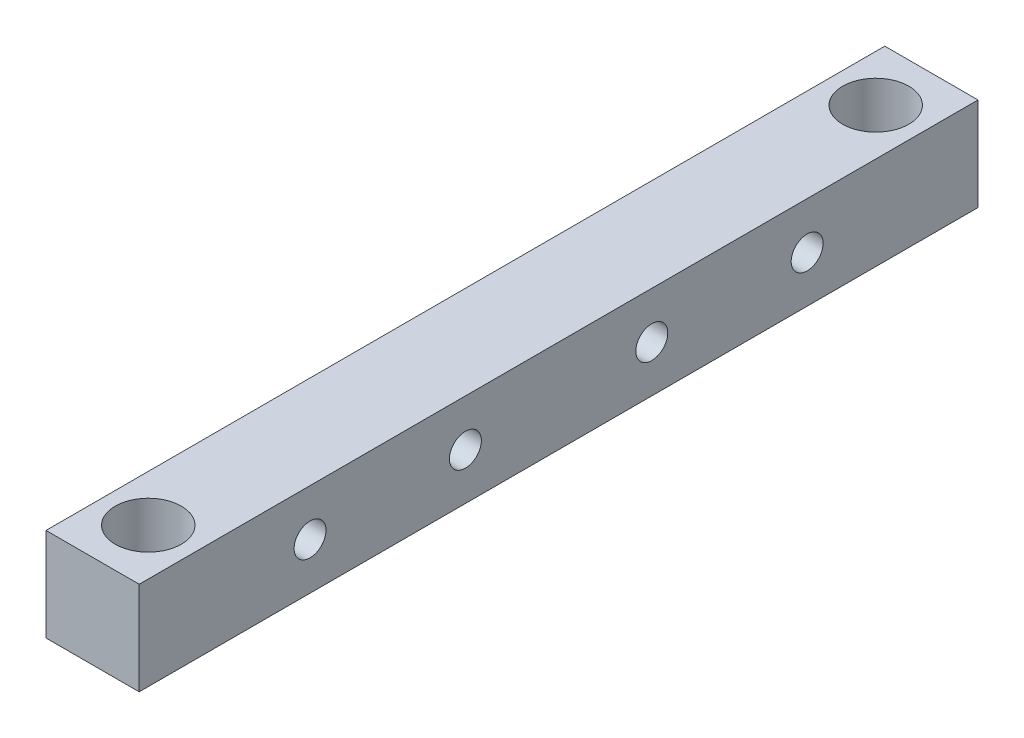
SolidWorks part; units mm, degrees
ref_plane "Front Plane" through (0, 0, 0) normal (0, 0, 1) x (1, 0, 0)
ref_plane "Top Plane" through (0, 0, 0) normal (0, 1, 0) x (1, 0, 0)
ref_plane "Right Plane" through (0, 0, 0) normal (1, 0, 0) x (0, 0, -1)
sketch "Sketch1" plane through (0, 0, 0) normal (0, 0, 1) x (1, 0, 0)
  line L1 (-4.7625, -4.7625) -> (4.7625, -4.7625)
  line L2 (-4.7625, -4.7625) -> (-4.7625, 4.7625)
  line L3 (-4.7625, 4.7625) -> (4.7625, 4.7625)
  line L4 (4.7625, -4.7625) -> (4.7625, 4.7625)
  line L5 (-4.7625, -4.7625) -> (4.7625, 4.7625) construction
  line L6 (-4.7625, 4.7625) -> (4.7625, -4.7625) construction
  point P0 (0, 0)
  dimension "D1" = 9.525
  dimension "D2" = 9.525
extrude "Boss-Extrude1" add sketch "Sketch1" along normal mid plane 85.725
sketch "Sketch3" plane through (0, 4.7625, 0) normal (0, 1, 0) x (1, 0, 0)
  line L0 (0, 0) -> (0, 37.1729) construction
  dimension "D1" = 37.1729
hole_wizard "1/4 Clearance Hole1" positions "Sketch5" profile "Sketch4" hole size "1/4" standard "ANSI Inch" end condition through all
sketch "Sketch5" plane through (0, 4.7625, 0) normal (0, 1, 0) x (1, 0, 0)
  point P0 (0, 37.1729)
sketch "Sketch4" plane through (0, 4.7625, -37.1729) normal (1, 0, 0) x (0, 0, 1)
  line L0 (0, 0) -> (0, 9.525)
  line L1 (0, 9.525) -> (3.3782, 9.525)
  line L2 (3.3782, 9.525) -> (3.3782, 0)
  line L5 (3.3782, 0) -> (0, 0)
  line L11 (0, -6.35) -> (0, 107.95) construction
  dimension "Thru Hole Dia." = 6.7564
  dimension "Thru Hole Depth" = 9.525
mirror "Mirror1" about plane through (0, 0, 0) normal (0, 0, 1) of "1/4 Clearance Hole1"
sketch "Sketch9" plane through (4.7625, 0, 0) normal (1, 0, 0) x (0, 0, -1)
  line L0 (0, 0) -> (9.525, 0) construction
  line L1 (9.525, 0) -> (25.4, 0) construction
  dimension "D1" = 9.525
  dimension "D2" = 25.4
hole_wizard "#4 Clearance Hole1" positions "Sketch11" profile "Sketch10" hole size "#4" standard "ANSI Inch" end condition through all
sketch "Sketch11" plane through (4.7625, 0, 0) normal (1, 0, 0) x (0, 0, -1)
  point P0 (9.525, 0)
  point P3 (25.4, 0)
sketch "Sketch10" plane through (4.7625, 0, -9.525) normal (0, 1, 0) x (0, 0, -1)
  line L0 (0, 0) -> (0, 9.525)
  line L1 (0, 9.525) -> (1.6319, 9.525)
  line L2 (1.6319, 9.525) -> (1.6319, 0)
  line L5 (1.6319, 0) -> (0, 0)
  line L11 (0, -6.35) -> (0, 107.95) construction
  dimension "Thru Hole Dia." = 3.2639
  dimension "Thru Hole Depth" = 9.525
mirror "Mirror2" about plane through (0, 0, 0) normal (0, 0, 1) of "#4 Clearance Hole1"
